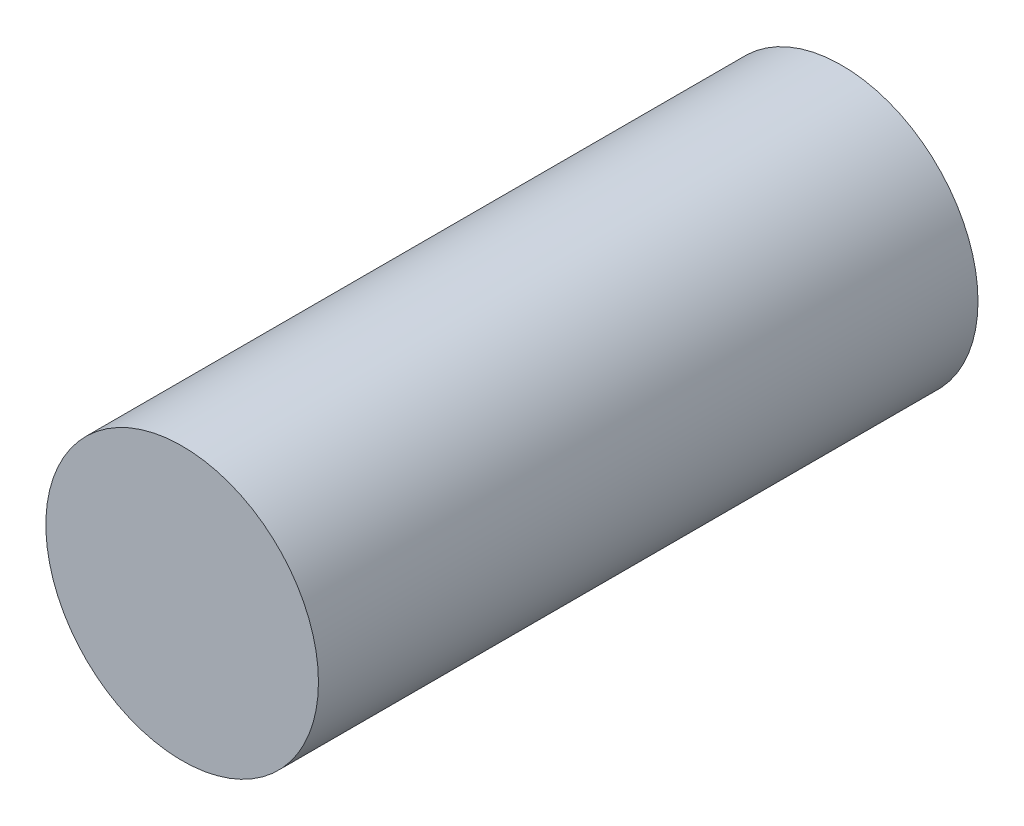
SolidWorks part; units mm, degrees
ref_plane "Front Plane" through (0, 0, 0) normal (0, 0, 1) x (1, 0, 0)
ref_plane "Top Plane" through (0, 0, 0) normal (0, 1, 0) x (1, 0, 0)
ref_plane "Right Plane" through (0, 0, 0) normal (1, 0, 0) x (0, 0, -1)
sketch "Sketch1" plane through (0, 0, 0) normal (0, 0, 1) x (1, 0, 0)
  circle A0 centre (0, 0) radius 1.55
extrude "Boss-Extrude1" add sketch "Sketch1" along normal blind 7.5
